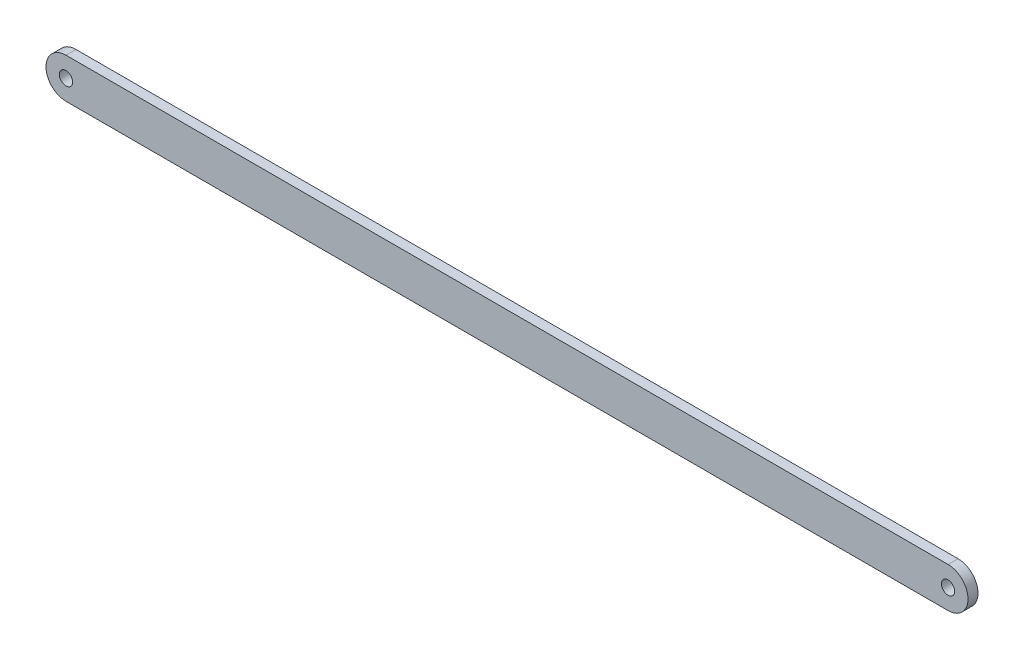
SolidWorks part; units mm, degrees
ref_plane "Front Plane" through (0, 0, 0) normal (0, 0, 1) x (1, 0, 0)
ref_plane "Top Plane" through (0, 0, 0) normal (0, 1, 0) x (1, 0, 0)
ref_plane "Right Plane" through (0, 0, 0) normal (1, 0, 0) x (0, 0, -1)
sketch "Sketch1" plane through (0, 0, 0) normal (0, 0, 1) x (1, 0, 0)
  line L0 (-35.3127, 0) -> (229.6873, 0) construction
  line L1 (-35.3127, 6) -> (229.6873, 6)
  line L2 (-35.3127, -6) -> (229.6873, -6)
  arc A0 (-35.3127, 6) -> (-35.3127, -6) centre (-35.3127, 0) ccw
  arc A1 (229.6873, -6) -> (229.6873, 6) centre (229.6873, 0) ccw
  circle A2 centre (-35.3127, 0) radius 2
  circle A3 centre (229.6873, 0) radius 2
  point P3 (97.1873, 0)
  dimension "D3" = 4
  dimension "D4" = 4
  dimension "D1" = 265
  dimension "D2" = 12
extrude "Boss-Extrude3" add sketch "Sketch1" along normal blind 3
